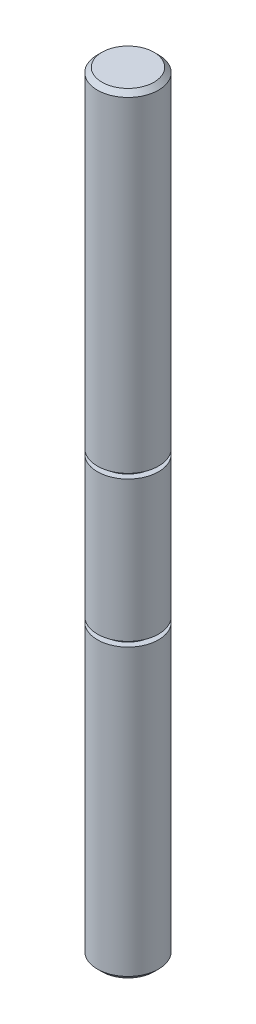
SolidWorks part; units mm, degrees
material "AISI 316 Annealed Stainless Steel Bar (SS)"
ref_plane "Front Plane" through (0, 0, 0) normal (0, 0, 1) x (1, 0, 0)
ref_plane "Top Plane" through (0, 0, 0) normal (0, 1, 0) x (1, 0, 0)
ref_plane "Right Plane" through (0, 0, 0) normal (1, 0, 0) x (0, 0, -1)
sketch "Sketch1" plane through (0, 0, 0) normal (0, 1, 0) x (1, 0, 0)
  circle A0 centre (0, 0) radius 5
  dimension "D1" = 10
extrude "Boss-Extrude1" add sketch "Sketch1" along normal blind 126
chamfer "Chamfer1" distance 0.75 angle 45 2 edges at (0, 126, 5) (0, 0, 5)
sketch "Sketch2" plane through (0, 0, 0) normal (0, 0, 1) x (1, 0, 0)
  line L0 (0, 111.5064) -> (0, 69.246) construction
  line L1 (-5, 125.25) -> (-5, 0.75) construction
  line L2 (-5, 47.4) -> (-4, 47.4)
  line L3 (-5, 47.4) -> (-5, 48.2)
  line L4 (-5, 48.2) -> (-4, 48.2)
  line L5 (-4, 47.4) -> (-4, 48.2)
  line L6 (-5, 71.2) -> (-5, 72)
  line L7 (-5, 72) -> (-4, 72)
  line L8 (-4, 71.2) -> (-4, 72)
  line L9 (-5, 71.2) -> (-4, 71.2)
  line L10 (4.25, 126) -> (-4.25, 126) construction
  dimension "D1" = 1
  dimension "D2" = 0.8
  dimension "D3" = 54
  dimension "D5" = 23
  dimension "D4" = 2
revolve "Cut-Revolve1" cut sketch "Sketch2" angle 360 about L0
